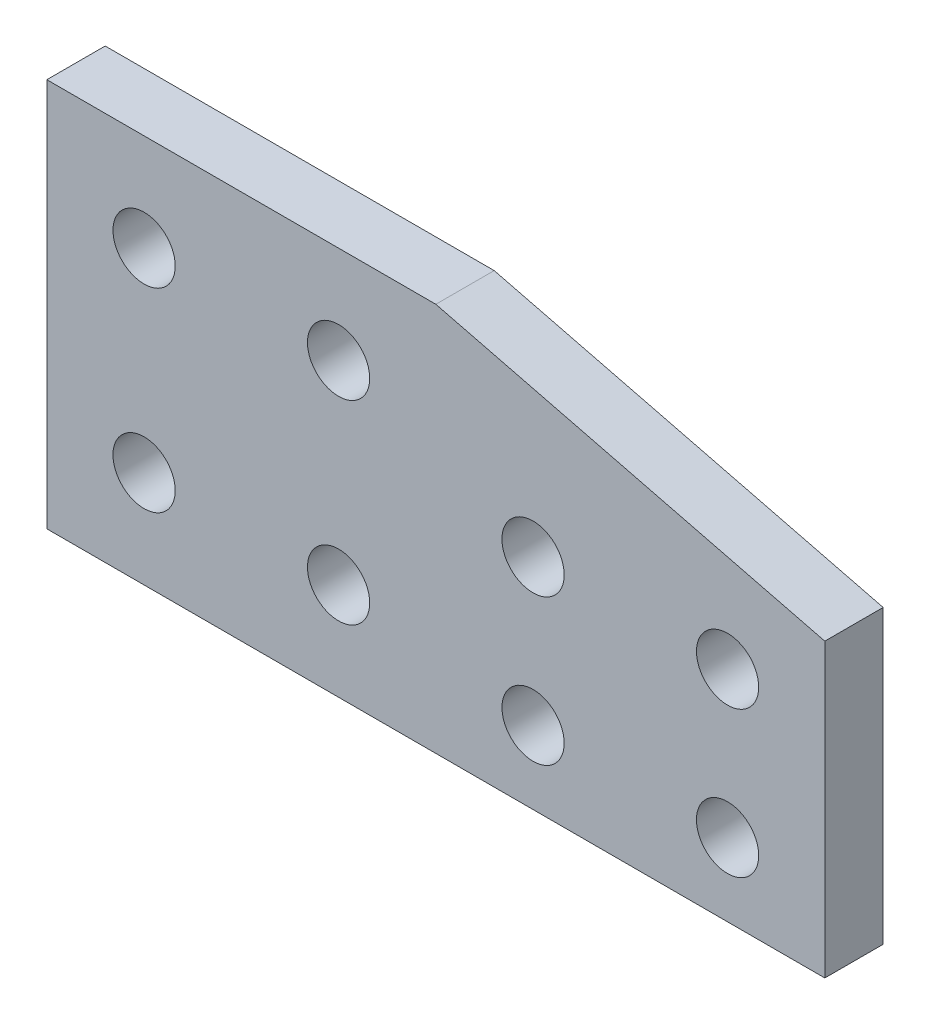
SolidWorks part; units mm, degrees
ref_plane "前视基准面" through (0, 0, 0) normal (0, 0, 1) x (1, 0, 0)
ref_plane "上视基准面" through (0, 0, 0) normal (0, 1, 0) x (1, 0, 0)
ref_plane "右视基准面" through (0, 0, 0) normal (1, 0, 0) x (0, 0, -1)
other "Configuration Table"
sketch "草图1" plane through (0, 0, 0) normal (0, 0, 1) x (1, 0, 0)
  line L0 (0, 0) -> (20, 0)
  line L1 (20, 0) -> (20, -5)
  line L2 (20, -5) -> (40, -5)
  line L3 (40, -5) -> (40, -20)
  line L4 (40, -20) -> (0, -20)
  line L5 (0, -20) -> (0, 0)
  dimension "D1" = 20
  dimension "D2" = 5
  dimension "D3" = 15
  dimension "D4" = 20
extrude "凸台-拉伸1" add sketch "草图1" along normal blind 3
sketch "草图2" plane through (0, 0, 3) normal (0, 0, 1) x (1, 0, 0)
  line L0 (20, -10) -> (0, -10) construction
  line L3 (10, 0) -> (10, -10) construction
  line L4 (20, 0) -> (0, 0) construction
  line L5 (30, -5) -> (30, -20) construction
  line L6 (40, -5) -> (20, -5) construction
  line L7 (0, -20) -> (40, -20) construction
  line L8 (40, -12.5) -> (30, -12.5) construction
  line L9 (40, -20) -> (40, -5) construction
  circle A0 centre (5, -5) radius 1.6
  circle A1 centre (35, -8.75) radius 1.6
  circle A2 centre (5, -15) radius 1.6
  circle A3 centre (15, -5) radius 1.6
  circle A4 centre (15, -15) radius 1.6
  circle A5 centre (35, -16.25) radius 1.6
  circle A6 centre (25, -16.25) radius 1.6
  circle A7 centre (25, -8.75) radius 1.6
  dimension "D1" = 3.2
  dimension "D4" = 3.2
  dimension "D2" = 5
  dimension "D3" = 5
  dimension "D5" = 3.75
  dimension "D6" = 5
  dimension "D7" = 10
extrude "切除-拉伸1" cut sketch "草图2" against normal through all
sketch "草图4" plane through (0, 0, 3) normal (0, 0, 1) x (1, 0, 0)
  line L0 (20, 0) -> (40, -5)
  line L1 (40, -5) -> (20, -5)
  line L2 (20, -5) -> (20, 0)
extrude "凸台-拉伸2" add sketch "草图4" against normal blind 3
